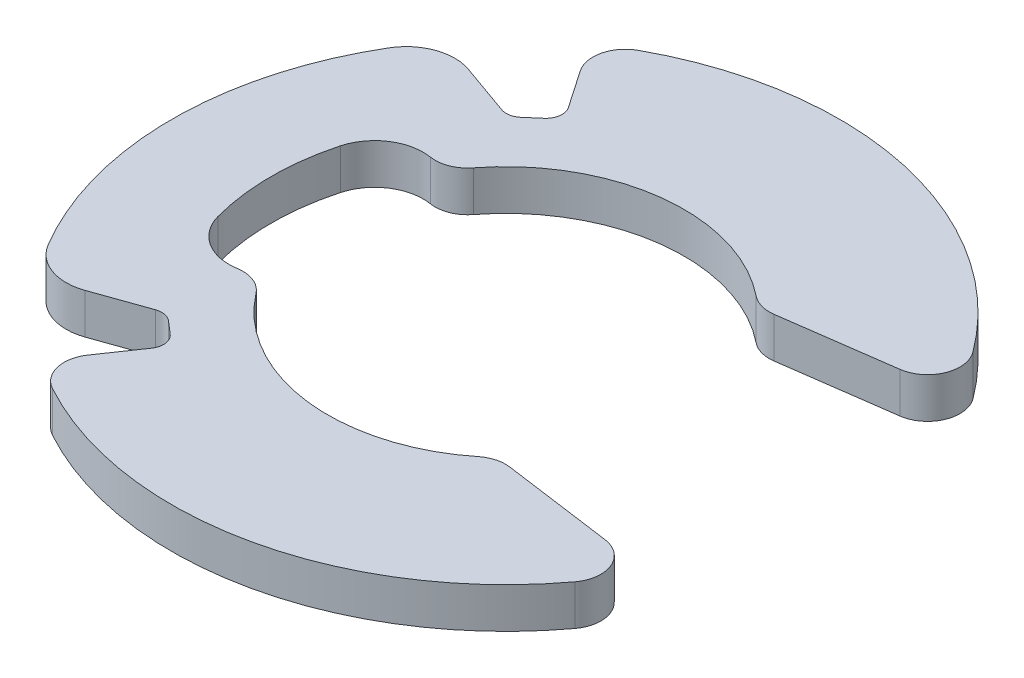
SolidWorks part; units mm, degrees
material "Plain Carbon Steel"
ref_plane "Front" through (0, 0, 0) normal (0, 0, 1) x (1, 0, 0)
ref_plane "Top" through (0, 0, 0) normal (0, 1, 0) x (1, 0, 0)
ref_plane "Right" through (0, 0, 0) normal (1, 0, 0) x (0, 0, -1)
sketch "Sketch1" plane through (0, 0, 0) normal (0, 1, 0) x (1, 0, 0)
  line L1 (-10.4775, 0) -> (-7.366, 0)
  line L2 (0, 0) -> (-12.2533, 0) construction
  line L17 (4.2692, 4.1469) -> (7.7407, 4.6274)
  line L18 (-5.3858, 7.7232) -> (-4.5747, 6.5382)
  line L19 (-4.6622, 5.8665) -> (-5.0565, 5.5266)
  line L20 (-5.558, 5.4326) -> (-7.1874, 6.0106)
  arc A49 (-7.1109, 1.9216) -> (-7.366, 0) centre (0, 0) ccw
  arc A50 (-5.3946, 3.0282) -> (-7.1109, 1.9216) centre (-5.6397, 1.524) ccw
  arc A51 (-5.3946, 3.0282) -> (-4.4263, 3.4108) centre (-5.2311, 4.0309) ccw
  arc A52 (3.4946, 4.3605) -> (-4.4263, 3.4108) centre (0, 0) ccw
  arc A53 (3.4946, 4.3605) -> (4.2692, 4.1469) centre (4.1299, 5.1533) ccw
  arc A54 (7.7407, 4.6274) -> (8.4176, 6.2387) centre (7.6014, 5.6338) ccw
  arc A55 (8.4176, 6.2387) -> (-5.0357, 9.188) centre (0, 0) ccw
  arc A56 (-5.0357, 9.188) -> (-5.3858, 7.7232) centre (-4.5474, 8.2971) ccw
  arc A57 (-4.6622, 5.8665) -> (-4.5747, 6.5382) centre (-4.9939, 6.2513) ccw
  arc A58 (-5.558, 5.4326) -> (-5.0565, 5.5266) centre (-5.3882, 5.9114) ccw
  arc A59 (-7.1874, 6.0106) -> (-9.0069, 5.3528) centre (-7.6968, 4.5743) ccw
  arc A60 (-9.0069, 5.3528) -> (-10.4775, 0) centre (0, 0) ccw
  dimension "D1" = 5.588
  dimension "D3" = 7.366
  dimension "D5" = 1.016
  dimension "D6" = 1.524
  dimension "D7" = 7.366
  dimension "D8" = 10.4775
  dimension "D10" = 10.4775
  dimension "D11" = 4.5743
  dimension "D12" = 5.6397
  dimension "D13" = 1.524
  dimension "D14" = 3.5224
  dimension "D15" = 7.88
  dimension "D16" = 0.508
  dimension "D9" = 3.1115
  dimension "D17" = 1.6294
  dimension "D20" = 0.5205
  dimension "D42" = 7.9797
  dimension "D43" = 1.185
  dimension "D44" = 0.8111
extrude "Extrude1" add sketch "Sketch1" along normal mid plane 1.27
mirror "Mirror1" about plane through (-10.4775, 0.635, 0) normal (0, 0, -1) of bodies 104
